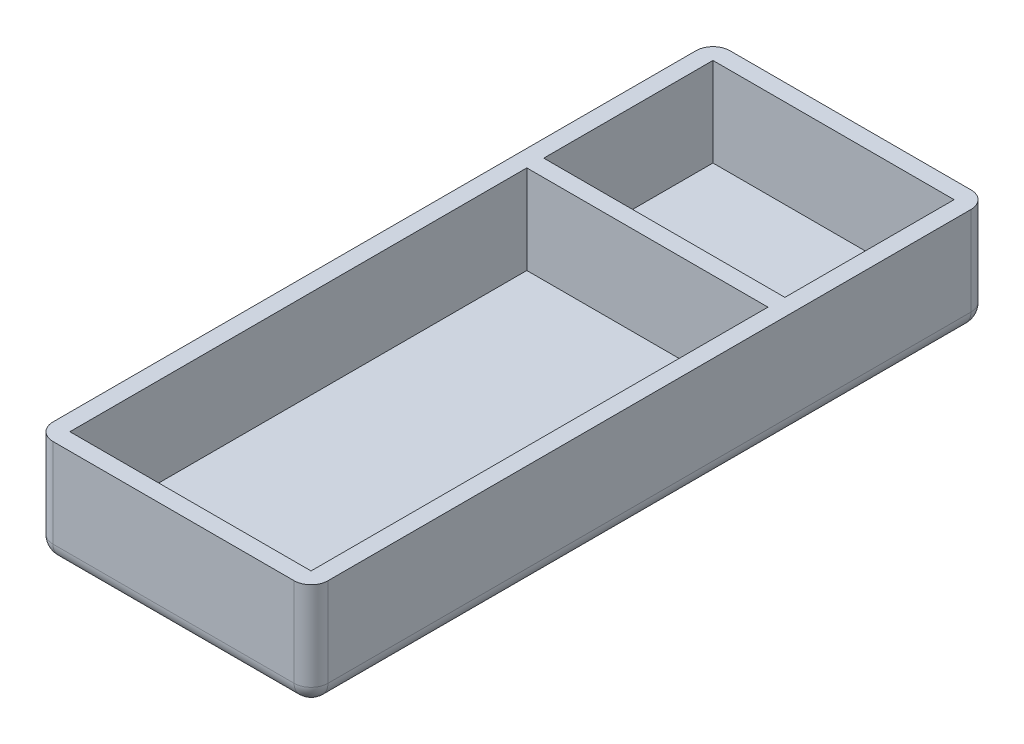
SolidWorks part; units mm, degrees
ref_plane "Front Plane" through (0, 0, 0) normal (0, 0, 1) x (1, 0, 0)
ref_plane "Top Plane" through (0, 0, 0) normal (0, 1, 0) x (1, 0, 0)
ref_plane "Right Plane" through (0, 0, 0) normal (1, 0, 0) x (0, 0, -1)
sketch "Sketch2" plane through (0, 0, 0) normal (0, 1, 0) x (1, 0, 0)
  line L0 (-32.5, 80) -> (32.5, -80) construction
  line L1 (-32.5, 80) -> (32.5, 80)
  line L2 (-32.5, 80) -> (-32.5, -80)
  line L3 (-32.5, -80) -> (32.5, -80)
  line L4 (32.5, 80) -> (32.5, -80)
  line L5 (-32.5, -80) -> (32.5, 80) construction
  point P4 (0, 0)
  dimension "D1" = 65
  dimension "D2" = 160
extrude "Base" add sketch "Sketch2" along normal blind 25
sketch "Sketch3" plane through (0, 25, 0) normal (0, 1, 0) x (1, 0, 0)
  line L0 (32.5, -80) -> (32.5, 80) construction
  line L1 (-28.5, -76) -> (28.5, -76)
  line L2 (-28.5, -76) -> (-28.5, 76)
  line L3 (-28.5, 76) -> (28.5, 76)
  line L4 (28.5, -76) -> (28.5, 76)
  line L5 (-28.5, -76) -> (28.5, 76) construction
  line L6 (-28.5, 76) -> (28.5, -76) construction
  line L7 (32.5, 80) -> (-32.5, 80) construction
  point P0 (0, 0)
  dimension "D1" = 4
  dimension "D2" = 4
extrude "Inside Space" cut sketch "Sketch3" against normal offset from surface (21 mm away) 4 up to face at (0, 0, 0)
sketch "Sketch4" plane through (0, 4, 0) normal (0, 1, 0) x (1, 0, 0)
  line L0 (-28.5, 76) -> (-28.5, -76) construction
  line L1 (-28.5, 36) -> (28.5, 36)
  line L2 (-28.5, 36) -> (-28.5, 32)
  line L3 (-28.5, 32) -> (28.5, 32)
  line L4 (28.5, 36) -> (28.5, 32)
  line L5 (28.5, -76) -> (28.5, 76) construction
  line L6 (-28.5, 76) -> (28.5, 76) construction
  dimension "D1" = 40
  dimension "D2" = 4
extrude "Battery Wall" add sketch "Sketch4" along normal up to surface (21 mm away) up to face at (0, 25, 0)
fillet "Fillet1" radius 4 8 edges at (0, 0, 80) (32.5, 12.5, 80) (-32.5, 12.5, 80) (-32.5, 0, 0) (-32.5, 12.5, -80) (0, 0, -80) (32.5, 0, 0) (32.5, 12.5, -80)
